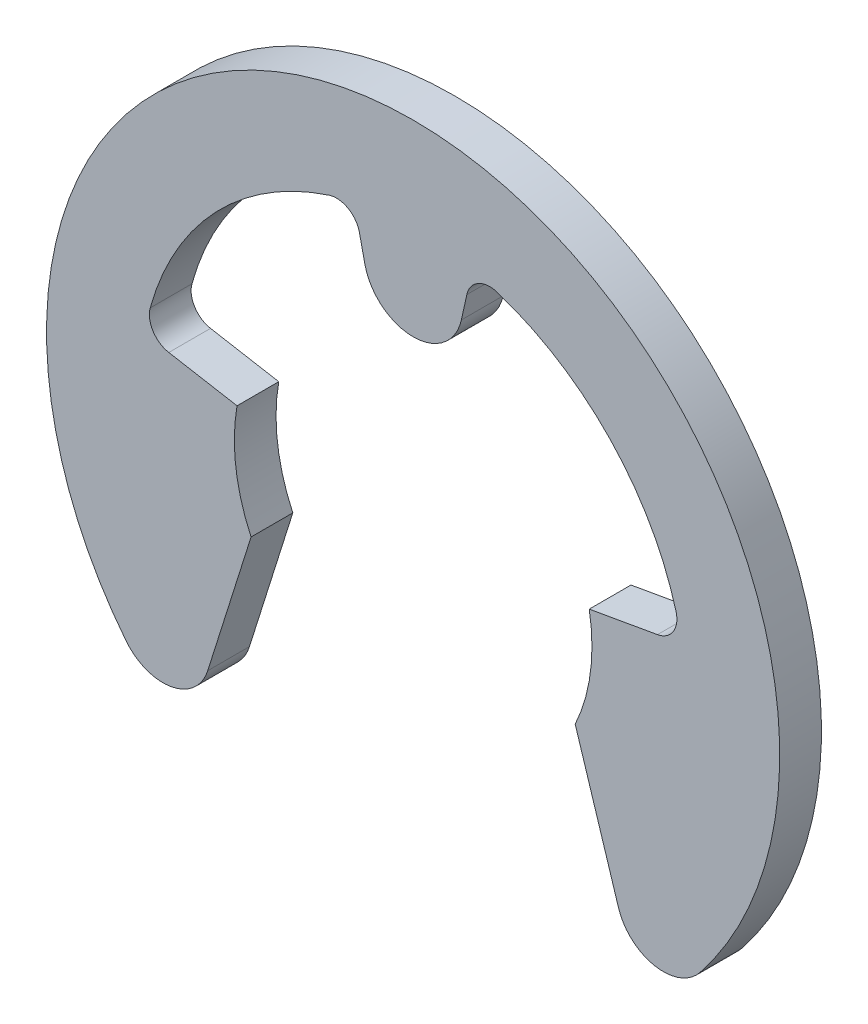
SolidWorks part; units mm, degrees
ref_plane "Plane1" through (0, 0, 0) normal (0, 0, 1) x (1, 0, 0)
ref_plane "Plane2" through (0, 0, 0) normal (0, 1, 0) x (1, 0, 0)
ref_plane "Plane3" through (0, 0, 0) normal (1, 0, 0) x (0, 0, -1)
sketch "BodySke" plane through (0, 0, 0) normal (0, 0, 1) x (1, 0, 0)
  line L0 (-0.7581, 0) -> (0.7581, 0) construction
  line L1 (0, 0) -> (0, 6.15) construction
  line L2 (0, 0) -> (0.1641, 0.7402) construction
  line L3 (0, 0) -> (5.5738, -2.5991) construction
  line L4 (0, 0) -> (-0.1641, 0.7402) construction
  line L5 (0, 0) -> (-5.5738, -2.5991) construction
  line L6 (2.9544, 0.5209) -> (4.0994, 0.7228)
  line L7 (-2.9544, 0.5209) -> (-4.0994, 0.7228)
  line L8 (0, 0) -> (6.0566, 1.0679) construction
  line L9 (2.7189, -1.2679) -> (3.4462, -3.5744)
  line L10 (-2.7189, -1.2679) -> (-3.4462, -3.5744)
  line L11 (0.809, 3.6493) -> (0.901, 4.064)
  line L12 (-0.809, 3.6493) -> (-0.901, 4.064)
  line L13 (0, 0) -> (-6.0566, 1.0679) construction
  circle A0 centre (0, 0) radius 3 construction
  arc A1 (4.4107, 1.2152) -> (1.4064, 4.3535) centre (0, 0) ccw
  arc A2 (4.8136, -3.8278) -> (-4.8136, -3.8278) centre (0, 0) ccw
  arc A3 (2.7189, -1.2679) -> (2.9544, 0.5209) centre (0, 0) ccw
  arc A4 (-1.4064, 4.3535) -> (-4.4107, 1.2152) centre (0, 0) ccw
  arc A5 (4.0994, 0.7228) -> (4.4107, 1.2152) centre (4.0311, 1.1106) ccw
  arc A7 (1.4064, 4.3535) -> (0.901, 4.064) centre (1.2854, 3.9788) ccw
  arc A8 (-2.9544, 0.5209) -> (-2.7189, -1.2679) centre (0, 0) ccw
  arc A9 (-4.4107, 1.2152) -> (-4.0994, 0.7228) centre (-4.0311, 1.1106) ccw
  arc A10 (-0.809, 3.6493) -> (0.809, 3.6493) centre (0, 3.8287) ccw
  arc A11 (-0.901, 4.064) -> (-1.4064, 4.3535) centre (-1.2854, 3.9788) ccw
  arc A12 (-4.8136, -3.8278) -> (-3.4462, -3.5744) centre (-4.1972, -3.3376) ccw
  arc A13 (3.4462, -3.5744) -> (4.8136, -3.8278) centre (4.1972, -3.3376) ccw
  dimension "CavityDia" = 17.7
  dimension "TipRad" = 1.425
  dimension "CavityFilletRad" = 0.7125
  dimension "D3" = 25
  dimension "D4" = 35
  dimension "D1" = 35
  dimension "D2" = 160
extrude "Body" add sketch "BodySke" against normal blind 0.7
equation "' \"Thickness@Body\" = 0.2"
equation "' \"GrooveDia@BodySke\" = 0.8"
equation "' \"OutsideDia@BodySke\" = 2.25"
equation "' \"Thickness@Body\" = 2.5"
equation "' \"GrooveDia@BodySke\" = 30"
equation "' \"OutsideDia@BodySke\" = 52.6"
equation "\"CavityDia@BodySke\" = (\"OutsideDia@BodySke\"  + \"GrooveDia@BodySke\") / 2 "
equation "\"CavityFilletRad@BodySke\" =  (\"CavityDia@BodySke\" - \"GrooveDia@BodySke\") / 2 * 0.25"
equation "\"TipRad@BodySke\" = (\"OutsideDia@BodySke\"  - \"GrooveDia@BodySke\") / 2 * 0.25"
